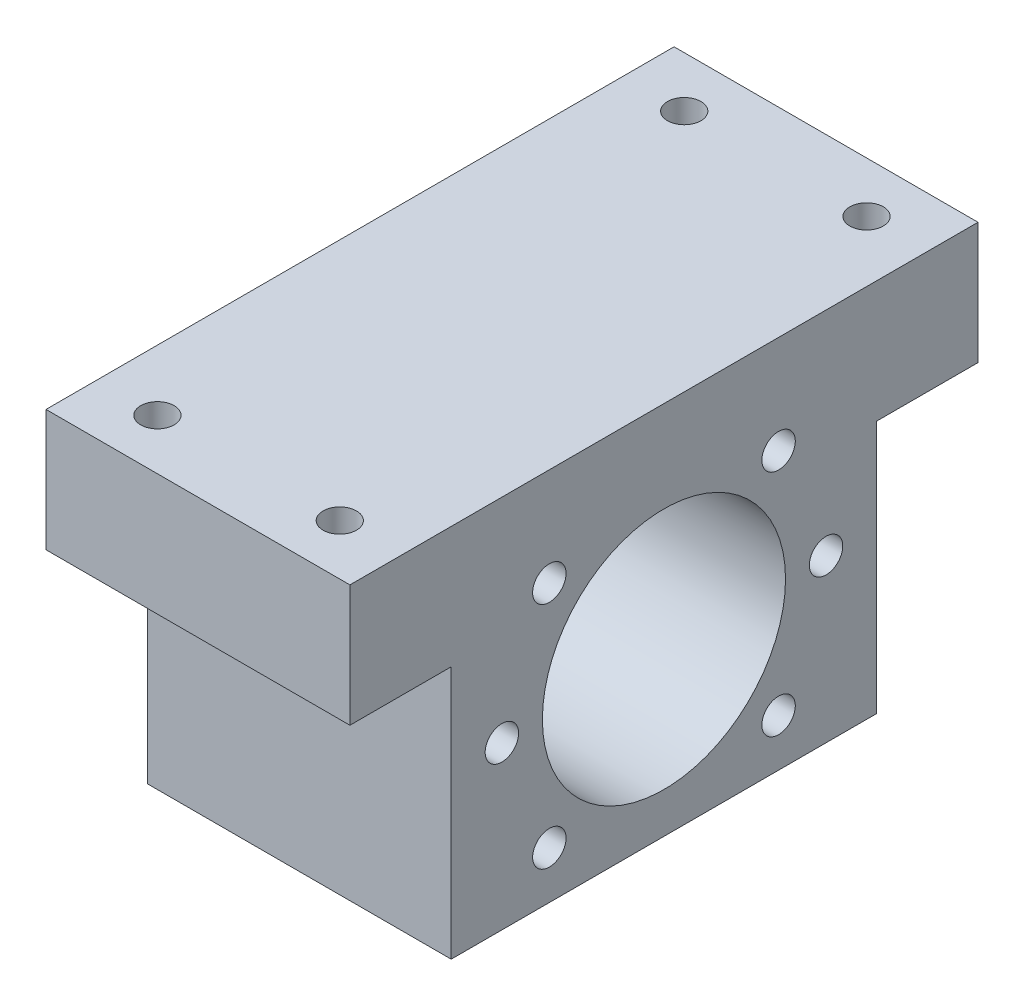
SolidWorks part; units mm, degrees
ref_plane "前视基准面" through (0, 0, 0) normal (0, 0, 1) x (1, 0, 0)
ref_plane "上视基准面" through (0, 0, 0) normal (0, 1, 0) x (1, 0, 0)
ref_plane "右视基准面" through (0, 0, 0) normal (1, 0, 0) x (0, 0, -1)
other "Configuration Table"
sketch "草图2" plane through (0, 0, 0) normal (1, 0, 0) x (0, 0, -1)
  line L1 (31, 41) -> (-31, 41)
  line L2 (31, 41) -> (31, -41)
  line L3 (31, -41) -> (-31, -41)
  line L4 (-31, 41) -> (-31, -41)
  line L5 (31, 41) -> (-31, -41) construction
  line L6 (31, -41) -> (-31, 41) construction
  point P0 (0, 0)
  dimension "D1" = 62
  dimension "D2" = 82
extrude "凸台-拉伸2" add sketch "草图2" along normal blind 30
sketch "草图3" plane through (0, 0, 0) normal (-1, 0, 0) x (0, 0, 1)
  line L0 (-31, 41) -> (31, 41) construction
  circle A0 centre (0, 20) radius 12
  dimension "D2" = 24
  dimension "D1" = 21
extrude "切除-拉伸1" cut sketch "草图3" against normal through all contours A0
sketch "草图7" plane through (30, 0, 0) normal (1, 0, 0) x (0, 0, -1)
  line L0 (-31, 29) -> (-21, 29)
  line L1 (-31, 41) -> (-31, -41) construction
  line L2 (-21, 29) -> (-21, 4)
  line L3 (-21, 4) -> (21, 4)
  line L4 (21, 4) -> (21, 29)
  line L5 (21, 29) -> (31, 29)
  line L6 (31, -41) -> (31, 41) construction
  line L7 (31, 29) -> (31, -41)
  line L8 (31, -41) -> (-31, -41)
  line L9 (-31, -41) -> (31, -41) construction
  line L10 (-31, -41) -> (-31, 29)
  dimension "D1" = 42
  dimension "D2" = 25
  dimension "D3" = 10
  dimension "D4" = 70
  dimension "D5" = 70
extrude "切除-拉伸2" cut sketch "草图7" against normal through all
sketch "草图8" plane through (0, 29, 0) normal (0, -1, 0) x (1, 0, 0)
  line L0 (0, 0) -> (56.5751, 0) construction
  line L1 (0, 31) -> (30, 31) construction
  line L2 (15, 31) -> (15, -41.1724) construction
  line L3 (0, 21) -> (30, 21) construction
  line L4 (0, 21) -> (0, 31) construction
  circle A0 centre (6, 26) radius 2
  circle A1 centre (24, 26) radius 2
  circle A7 centre (24, -26) radius 2
  circle A8 centre (6, -26) radius 2
  dimension "D2" = 4
  dimension "D5" = 5
  dimension "D6" = 6
sketch "草图4" plane through (30, 0, 0) normal (1, 0, 0) x (0, 0, -1)
  circle A0 centre (-11.3137, 8.6863) radius 2.25
  circle A1 centre (11.3137, 31.3137) radius 2.25
  circle A2 centre (-11.3137, 31.3137) radius 2.25
  circle A3 centre (-16, 20) radius 2.25
  circle A4 centre (11.3137, 8.6863) radius 2.25
  circle A5 centre (16, 20) radius 2.25
hole_wizard "M4 螺纹孔1" positions "草图11" profile "草图12" tap size "M4" standard "GB" end condition through all
sketch "草图11" plane through (0, 0, 0) normal (-1, 0, 0) x (0, 0, 1)
  point P0 (-11.3137, 31.3137)
  point P3 (11.3137, 8.6863)
  point P6 (11.3137, 31.3137)
  point P9 (16, 20)
  point P12 (-11.3137, 8.6863)
  point P15 (-16, 20)
sketch "草图12" plane through (0, 31.3137, -11.3137) normal (0, 1, 0) x (0, 0, 1)
  line L0 (0, 0) -> (0, 30)
  line L1 (0, 30) -> (1.65, 30)
  line L2 (1.65, 30) -> (1.65, 0)
  line L5 (1.65, 0) -> (0, 0)
  line L11 (0, -6.35) -> (0, 107.95) construction
  dimension "通孔螺纹孔钻头直径" = 3.3
  dimension "通孔螺纹孔钻头深度" = 30
cosmetic thread "孔螺蚊线2" parameters "D2"=4
cosmetic thread "孔螺蚊线3" parameters "D2"=4
cosmetic thread "孔螺蚊线4" parameters "D2"=4
cosmetic thread "孔螺蚊线5" parameters "D2"=4
cosmetic thread "孔螺蚊线6" parameters "D2"=4
cosmetic thread "孔螺蚊线15" parameters "D2"=4
hole_wizard "M4 螺纹孔2" positions "草图13" profile "草图14" tap size "M4" standard "GB" end condition through all
sketch "草图13" plane through (0, 29, 0) normal (0, -1, 0) x (-1, 0, 0)
  point P6 (-6, 26)
  point P9 (-24, 26)
  point P15 (-6, -26)
  point P18 (-24, -26)
sketch "草图14" plane through (6, 29, -26) normal (1, 0, 0) x (0, 0, -1)
  line L0 (0, 0) -> (0, 12)
  line L1 (0, 12) -> (1.65, 12)
  line L2 (1.65, 12) -> (1.65, 0)
  line L5 (1.65, 0) -> (0, 0)
  line L11 (0, -6.35) -> (0, 107.95) construction
  dimension "通孔螺纹孔钻头直径" = 3.3
  dimension "通孔螺纹孔钻头深度" = 12
cosmetic thread "孔螺蚊线8" parameters "D2"=4
cosmetic thread "孔螺蚊线9" parameters "D2"=4
cosmetic thread "孔螺蚊线11" parameters "D2"=4
cosmetic thread "孔螺蚊线12" parameters "D2"=4
